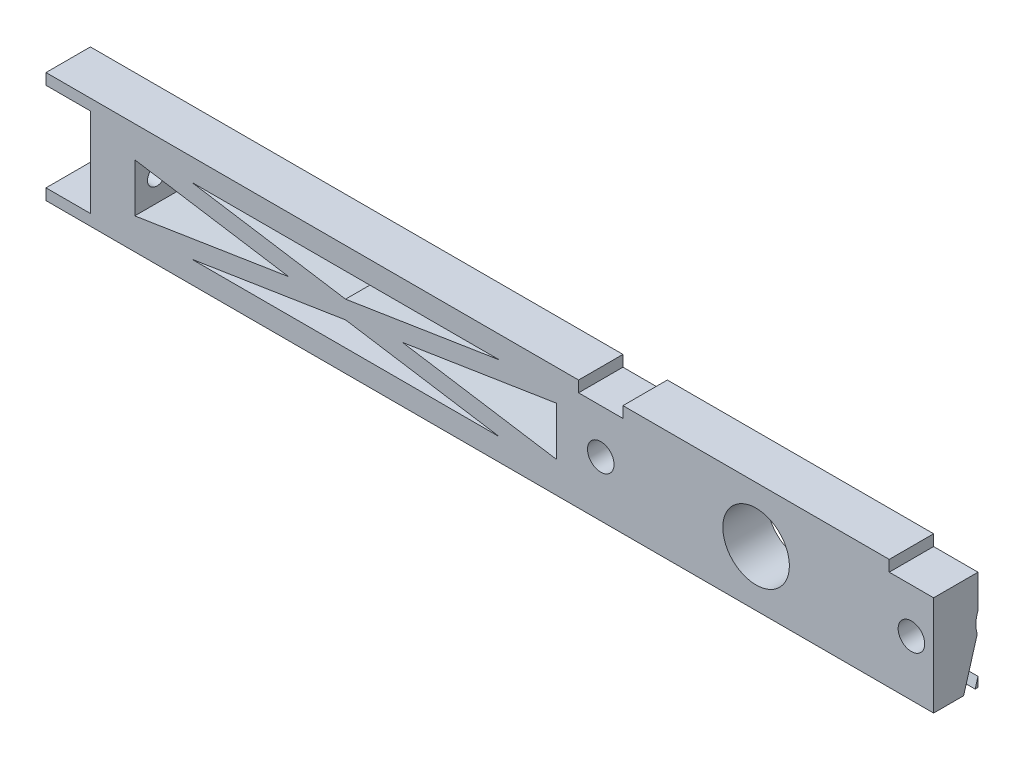
SolidWorks part; units mm, degrees
material "6061-T6 (SS)"
ref_plane "Front Plane" through (0, 0, 0) normal (0, 0, 1) x (1, 0, 0)
ref_plane "Top Plane" through (0, 0, 0) normal (0, 1, 0) x (1, 0, 0)
ref_plane "Right Plane" through (0, 0, 0) normal (1, 0, 0) x (0, 0, -1)
sketch "Sketch1" plane through (0, 0, 0) normal (0, 0, 1) x (1, 0, 0)
  line L0 (-89.0981, 3.508) -> (-28.7731, -6.017)
  line L1 (25.4, -7.9375) -> (-101.6, -7.9375)
  line L2 (25.4, -7.9375) -> (25.4, 7.9375)
  line L3 (25.4, 7.9375) -> (-101.6, 7.9375)
  line L4 (-101.6, -7.9375) -> (-101.6, 7.9375)
  line L5 (-88.9, 4.7625) -> (-28.575, 4.7625)
  line L6 (-88.9, 4.7625) -> (-88.9, -4.7625)
  line L7 (-88.9, -4.7625) -> (-28.575, -4.7625)
  line L8 (-28.575, 4.7625) -> (-28.575, -4.7625)
  line L9 (-88.9, 4.7625) -> (-28.575, -4.7625) construction
  line L10 (-88.9, -4.7625) -> (-28.575, 4.7625) construction
  line L17 (-88.7019, -6.017) -> (-28.3769, 3.508)
  line L18 (-88.7019, 6.017) -> (-28.3769, -3.508)
  line L19 (-89.0981, -3.508) -> (-28.7731, 6.017)
  circle A0 centre (0, 0) radius 4.7625
  arc A1 (-89.0981, 3.508) -> (-88.7019, 6.017) centre (-88.9, 4.7625) cw
  arc A2 (-28.7731, -6.017) -> (-28.3769, -3.508) centre (-28.575, -4.7625) ccw
  arc A3 (-88.7019, -6.017) -> (-89.0981, -3.508) centre (-88.9, -4.7625) cw
  arc A4 (-28.3769, 3.508) -> (-28.7731, 6.017) centre (-28.575, 4.7625) ccw
  point P7 (-58.7375, 0)
  dimension "D1" = 9.525
  dimension "D2" = 25.4
  dimension "D3" = 15.875
  dimension "D4" = 7.9375
  dimension "D5" = 127
  dimension "D6" = 3.175
  dimension "D7" = 3.175
  dimension "D8" = 28.575
  dimension "D9" = 12.7
  dimension "D14" = 1.27
  dimension "D15" = 1.27
extrude "Boss-Extrude1" add sketch "Sketch1" along normal blind 6.35
hole_wizard "CSK for #6 Flat Head Machine Screw (100)1" positions "Sketch3" profile "Sketch4" countersink size "#6" standard "ANSI Inch" end condition through all
sketch "Sketch3" plane through (0, 0, 0) normal (0, 0, -1) x (-1, 0, 0)
  line L0 (-25.4, -7.9375) -> (-25.4, 7.9375) construction
  line L1 (-25.4, 7.9375) -> (101.6, 7.9375) construction
  line L2 (-25.4, -7.9375) -> (101.6, -7.9375) construction
  point P0 (-22.225, 0)
  point P2 (-22.225, 0)
  point P21 (22.225, 0)
  point P26 (-25.4, 0)
  dimension "D1" = 3.175
  dimension "D2" = 7.9375
  dimension "D3" = 7.9375
  dimension "D5" = 22.225
sketch "Sketch4" plane through (22.225, 0, 0) normal (1, 0, 0) x (0, 1, 0)
  line L0 (0, 0) -> (0, 6.35)
  line L1 (0, 6.35) -> (1.8986, 6.35)
  line L2 (1.8986, 6.35) -> (1.8986, 1.38)
  line L3 (1.8986, 1.38) -> (3.5433, 0)
  line L5 (3.5433, 0) -> (0, 0)
  line L6 (-1.8987, 1.38) -> (-3.5433, 0) construction
  line L11 (0, -6.35) -> (0, 107.95) construction
  dimension "Thru Hole Dia." = 3.7973
  dimension "Thru Hole Depth" = 6.35
  dimension "Near C'Sink Dia." = 7.0866
  dimension "Near C'Sink Angle" = 100
ref_plane "Plane1" through (-38.1, 0, 0) normal (-1, 0, 0) x (0, 0, 1)
ref_plane "Plane2" through (0, 3.0467, 2.2815) normal (0, -0.8004, -0.5994) x (-1, 0, 0)
sketch "Sketch5" plane through (0, 0, 0) normal (0, 0, -1) x (-1, 0, 0)
  line L0 (101.6, -7.9375) -> (101.6, 7.9375) construction
  line L1 (-25.4, -7.9375) -> (101.6, -7.9375) construction
  line L3 (101.6, -6.35) -> (95.25, -6.35)
  line L5 (95.25, -6.35) -> (101.6, -6.35)
  line L6 (95.25, -6.35) -> (95.25, 6.35)
  line L7 (95.25, 6.35) -> (101.6, 6.35)
  line L8 (101.6, -6.35) -> (101.6, 6.35)
  line L9 (-25.4, 7.9375) -> (101.6, 7.9375) construction
  line M36 (101.6, -7.9375) -> (101.6, 7.9375)
  dimension "D1" = 1.5875
  dimension "D2" = 6.35
  dimension "D3" = 1.5875
extrude "Cut-Extrude1" cut sketch "Sketch5" against normal through all contours L7 L6 L3 M36
sketch "Sketch6" plane through (0, 0, 0) normal (0, 0, -1) x (-1, 0, 0)
  line L0 (-25.4, 7.9375) -> (101.6, 7.9375) construction
  line L1 (19.05, 7.9375) -> (25.4, 7.9375)
  line L2 (19.05, 7.9375) -> (19.05, 6.35)
  line L3 (19.05, 6.35) -> (25.4, 6.35)
  line L4 (25.4, 7.9375) -> (25.4, 6.35)
  line L7 (-25.4, 7.9375) -> (-19.05, 7.9375)
  line L8 (-25.4, 7.9375) -> (-25.4, 6.35)
  line L9 (-25.4, 6.35) -> (-19.05, 6.35)
  line L10 (-19.05, 7.9375) -> (-19.05, 6.35)
  dimension "D1" = 6.35
  dimension "D2" = 19.05
  dimension "D3" = 6.35
  dimension "D4" = 1.5875
extrude "Cut-Extrude2" cut sketch "Sketch6" against normal through all
mirror "Mirror3" about plane through (0, 3.0467, 2.2815) normal (0, -0.8004, -0.5994) of "Cut-Extrude2"
hole_wizard "Tap Drill for #6-32 Tap1" positions "Sketch8" profile "Sketch7" hole size "#6-32" standard "ANSI Inch"
sketch "Sketch8" plane through (-95.25, 0, 0) normal (-1, 0, 0) x (0, 0, 1)
  line L0 (6.35, 6.35) -> (0, 6.35) construction
  point P0 (3.175, 0)
  point P2 (3.175, 0)
  point P9 (3.175, 6.35)
  dimension "D1" = 7.9375
  dimension "D2" = 7.9375
sketch "Sketch7" plane through (-95.25, 0, 3.175) normal (0, 1, 0) x (0, 0, 1)
  line L0 (0, 0) -> (0, 7.1627)
  line L1 (0, 7.1627) -> (1.3525, 6.35)
  line L2 (1.3525, 6.35) -> (1.3525, 0)
  line L5 (1.3525, 0) -> (0, 0)
  line L10 (0, 7.1627) -> (-1.3525, 6.35) construction
  line L11 (0, -6.35) -> (0, 107.95) construction
  dimension "Hole Dia." = 2.7051
  dimension "Hole Depth" = 6.35
  dimension "Drill Angle" = 118
equation "\"D4@Sketch1\"=\"D3@Sketch1\"/2"
equation "\"D7@Sketch1\"=\"D6@Sketch1\""
equation "\"D3@Sketch3\" = \"D2@Sketch3\""
equation "\"Length\"= 5"
equation "\"Width\"= 5"
equation "\"D5@Sketch1\"=\"Length\""
